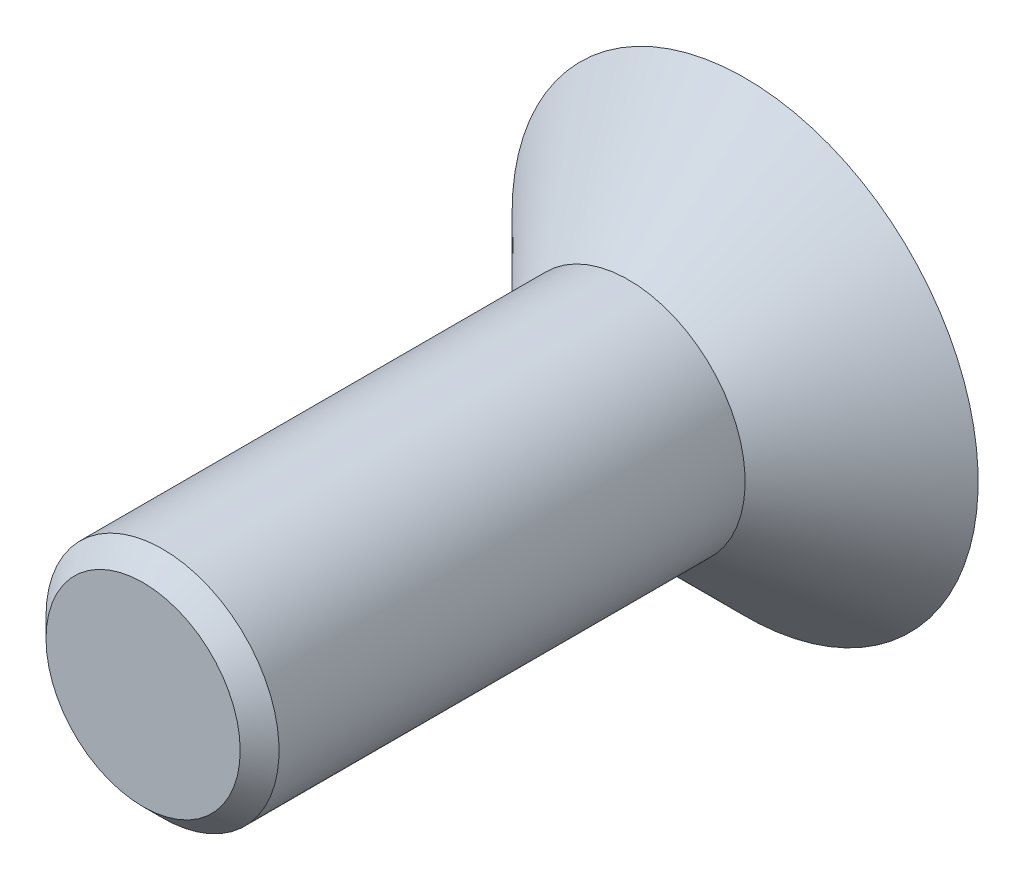
SolidWorks part; units mm, degrees
ref_plane "Front Plane" through (0, 0, 0) normal (0, 0, 1) x (1, 0, 0)
ref_plane "Top Plane" through (0, 0, 0) normal (0, 1, 0) x (1, 0, 0)
ref_plane "Right Plane" through (0, 0, 0) normal (1, 0, 0) x (0, 0, -1)
sketch "Sketch1" plane through (0, 0, 0) normal (0, 1, 0) x (1, 0, 0)
  line L0 (0, 48.7261) -> (0, -28.9809) construction
  line L1 (6, 0) -> (6, 25)
  line L2 (6, 25) -> (12, 31)
  line L3 (12, 31) -> (1, 31)
  line L4 (1, 31) -> (1, 29)
  line L5 (1, 29) -> (0, 29)
  line L6 (0, 0) -> (6, 0)
  line L7 (0, 29) -> (0, 0)
  dimension "D1" = 25
  dimension "D2" = 12
  dimension "D3" = 6
  dimension "D4" = 45
  dimension "D5" = 1
  dimension "D6" = 2
revolve "Revolve1" add sketch "Sketch1" angle 360 about L0
chamfer "Chamfer1" distance 1 angle 45 1 edges at (-6, 0, 0)
